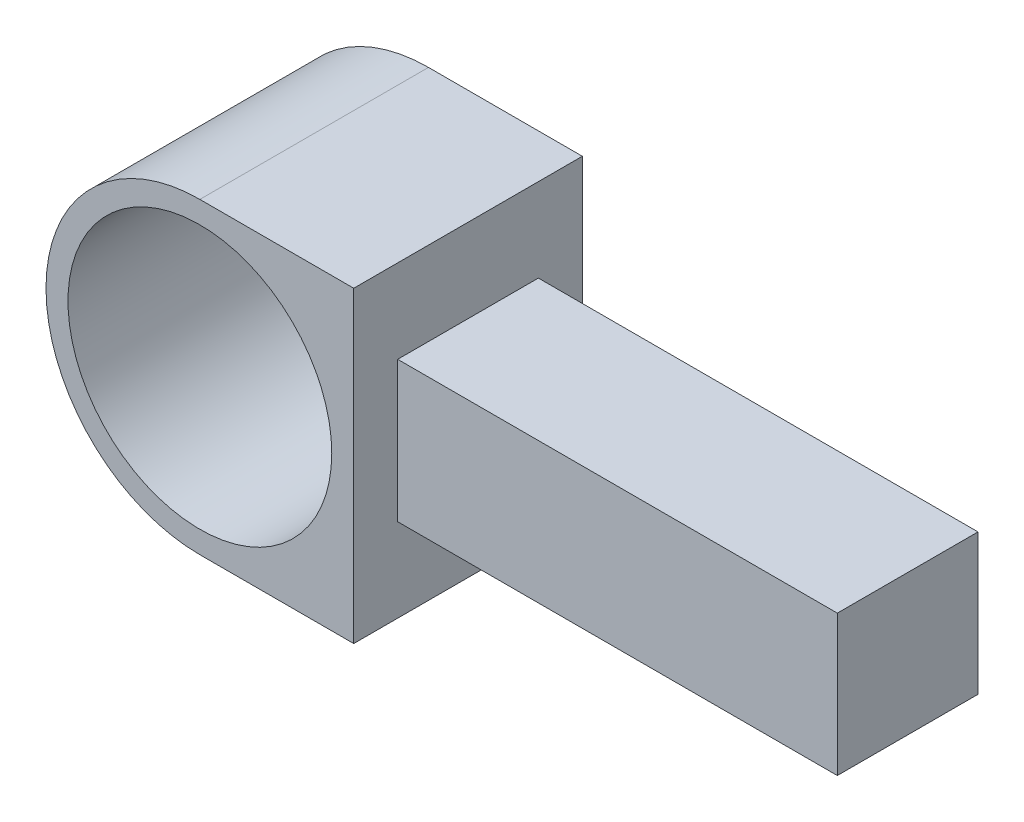
SolidWorks part; units mm, degrees
material "1350 合金"
ref_plane "前视基准面" through (0, 0, 0) normal (0, 0, 1) x (1, 0, 0)
ref_plane "上视基准面" through (0, 0, 0) normal (0, 1, 0) x (1, 0, 0)
ref_plane "右视基准面" through (0, 0, 0) normal (1, 0, 0) x (0, 0, -1)
sketch "草图1" plane through (0, 0, 0) normal (0, 0, 1) x (1, 0, 0)
  line L0 (0, 17.5) -> (17.5, 17.5)
  line L1 (0, -17.5) -> (17.5, -17.5)
  line L2 (17.5, 17.5) -> (17.5, -17.5)
  circle A0 centre (0, 0) radius 15 construction
  circle A1 centre (0, 0) radius 17.5 construction
  arc A2 (0, -17.5) -> (0, 17.5) centre (0, 0) cw
  dimension "D1" = 30
  dimension "D2" = 35
  dimension "D3" = 17.5
  dimension "D4" = 17.5
extrude "凸台-拉伸1" add sketch "草图1" along normal blind 26
sketch "草图2" plane through (0, 0, 26) normal (0, 0, 1) x (1, 0, 0)
  circle A0 centre (0, 0) radius 15
  dimension "D1" = 30
extrude "切除-拉伸1" cut sketch "草图2" against normal blind 26
sketch "草图3" plane through (17.5, 0, 0) normal (1, 0, 0) x (0, 0, -1)
  line L0 (-21, 8) -> (-5, 8)
  line L1 (-21, 8) -> (-21, -8)
  line L2 (-5, 8) -> (-5, -8)
  line L3 (-21, -8) -> (-5, -8)
  line L4 (-21, 8) -> (-5, -8) construction
  line L5 (-5, 8) -> (-21, -8) construction
  line L6 (-26, 17.5) -> (0, 17.5) construction
  line L7 (-26, -17.5) -> (-26, 17.5) construction
  point P1 (-13, 0)
  dimension "D1" = 16
  dimension "D2" = 9.5
  dimension "D3" = 5
extrude "凸台-拉伸2" add sketch "草图3" along normal blind 50
